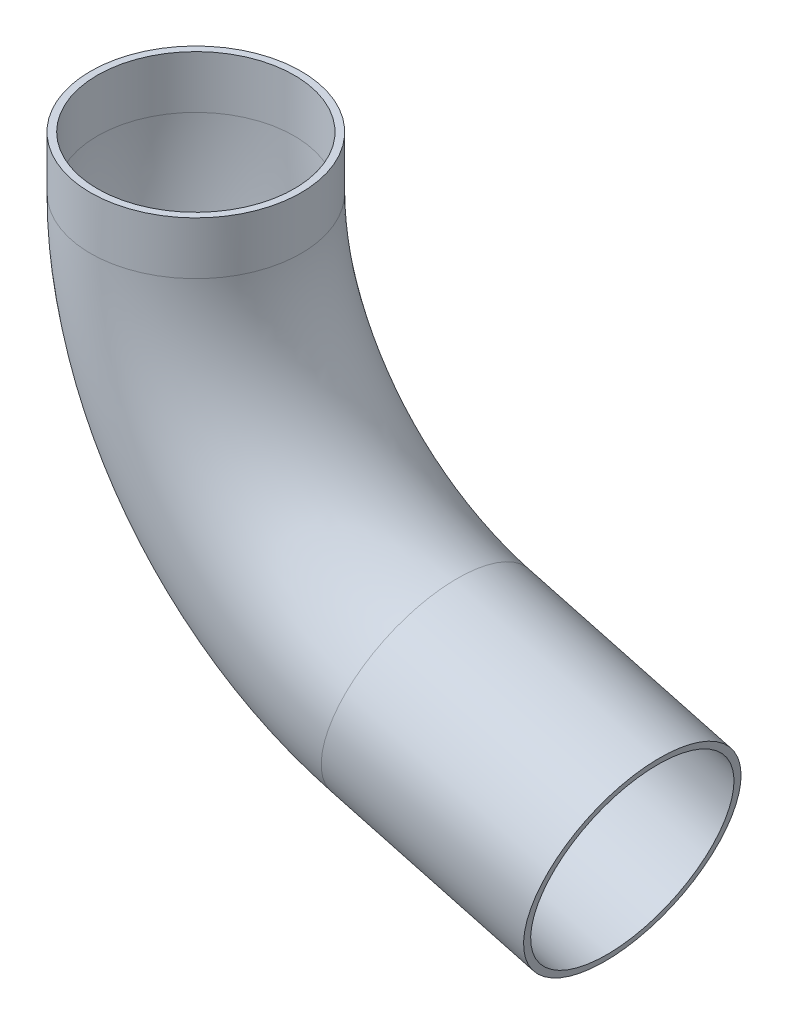
SolidWorks part; units mm, degrees
ref_plane "Front Plane" through (0, 0, 0) normal (0, 0, 1) x (1, 0, 0)
ref_plane "Top Plane" through (0, 0, 0) normal (0, 1, 0) x (1, 0, 0)
ref_plane "Right Plane" through (0, 0, 0) normal (1, 0, 0) x (0, 0, -1)
sketch "Sketch1" plane through (0, 0, 0) normal (0, 0, 1) x (1, 0, 0)
  line L0 (0, 0) -> (0, -12.7)
  line L1 (56.478, -86.3035) -> (105.3017, -99.3858)
  line L3 (0, -15.875) -> (162.3981, -15.875) construction
  line L4 (0, -25.4) -> (162.3981, -25.4) construction
  arc A0 (0, -12.7) -> (56.478, -86.3035) centre (76.2, -12.7) ccw
  dimension "D2" = 12.7
  dimension "D1" = 76.2
  dimension "D3" = 9.525
  dimension "D4" = 50.546
  dimension "D5" = 75
  dimension "D11" = 15.875
sketch "Sketch2" plane through (0, 0, 0) normal (0, 1, 0) x (1, 0, 0)
  circle A0 centre (0, 0) radius 25.4
  circle A1 centre (0, 0) radius 23.749
  dimension "D1" = 50.8
  dimension "D2" = 1.651
sweep "Sweep1" add profiles "Sketch2" path "Sketch1"
